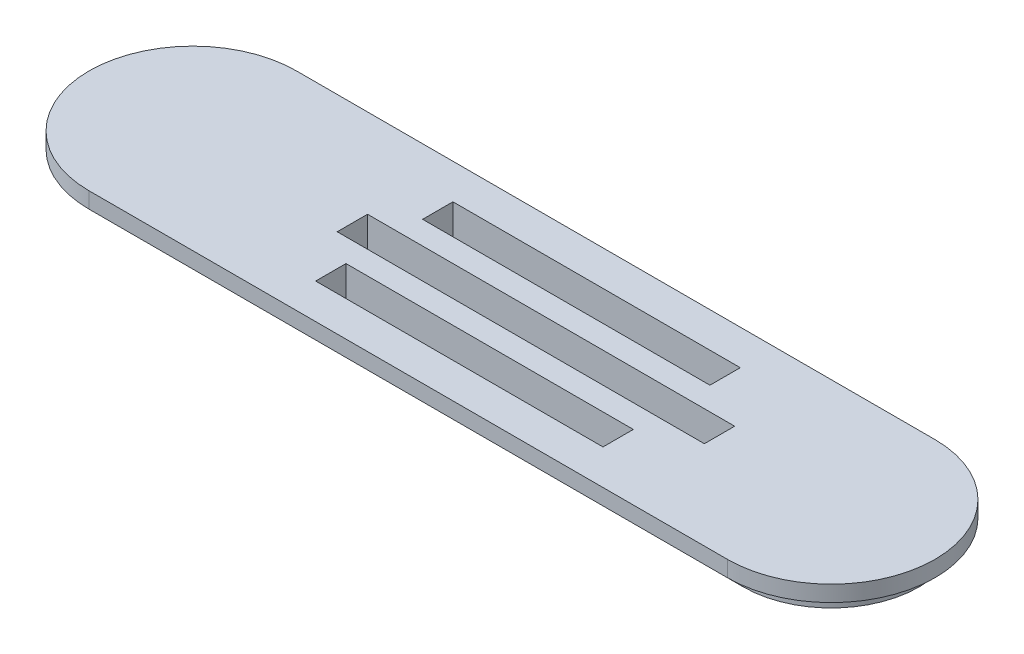
SolidWorks part; units mm, degrees
ref_plane "Front Plane" through (0, 0, 0) normal (0, 0, 1) x (1, 0, 0)
ref_plane "Top Plane" through (0, 0, 0) normal (0, 1, 0) x (1, 0, 0)
ref_plane "Right Plane" through (0, 0, 0) normal (1, 0, 0) x (0, 0, -1)
sketch "Sketch1" plane through (0, 0, 0) normal (0, 1, 0) x (1, 0, 0)
  line L0 (-100, 32.5) -> (100, 32.5)
  line L1 (-100, -32.5) -> (100, -32.5)
  line L6 (0, 21.5) -> (-40, 21.5)
  line L7 (-40, 21.5) -> (-40, 12)
  line L8 (-40, 12) -> (0, 12)
  line L9 (0, 12) -> (50, 12)
  line L10 (50, 12) -> (50, 21.5)
  line L11 (50, 21.5) -> (0, 21.5)
  line L12 (-50, 4.75) -> (0, 4.75)
  line L13 (0, 4.75) -> (65, 4.75)
  line L14 (65, 4.75) -> (65, -4.75)
  line L15 (65, -4.75) -> (0, -4.75)
  line L16 (0, -4.75) -> (-50, -4.75)
  line L17 (-50, -4.75) -> (-50, 4.75)
  line L21 (0, -12) -> (-40, -12)
  line L22 (-40, -12) -> (-40, -21.5)
  line L23 (-40, -21.5) -> (0, -21.5)
  line L24 (0, -21.5) -> (50, -21.5)
  line L25 (50, -21.5) -> (50, -12)
  line L26 (50, -12) -> (0, -12)
  line L27 (100, 13.6373) -> (100, -13.3202) construction
  line L28 (82.1775, 0) -> (117.959, 0) construction
  arc A0 (100, 32.5) -> (100, -32.5) centre (100, 0) cw
  arc A1 (-100, 32.5) -> (-100, -32.5) centre (-100, 0) ccw
  dimension "D7" = 4.75
  dimension "D1" = 32.5
  dimension "D2" = 32.5
  dimension "D3" = 100
  dimension "D4" = 100
  dimension "D25" = 9.5
  dimension "D26" = 9.5
  dimension "D27" = 9.5
  dimension "D28" = 50
  dimension "D29" = 0
  dimension "D30" = 0
  dimension "D31" = 40
  dimension "D32" = 65
  dimension "D33" = 0
  dimension "D34" = 0
  dimension "D35" = 50
  dimension "D36" = 40
  dimension "D37" = 0
  dimension "D38" = 0
  dimension "D39" = 50
  dimension "D40" = 11
  dimension "D41" = 11
extrude "Boss-Extrude1" add sketch "Sketch1" along normal blind 10
sketch "Sketch2" plane through (0, 0, 0) normal (0, 1, 0) x (1, 0, 0)
  line L0 (-100, 32.5) -> (100, 32.5)
  line L1 (100, -32.5) -> (-100, -32.5)
  line L2 (-100, 27.5) -> (100, 27.5)
  line L3 (-100, -27.5) -> (100, -27.5)
  arc A0 (100, 32.5) -> (100, -32.5) centre (100, 0) cw
  arc A1 (100, -32.5) -> (100, 32.5) centre (100, 0) ccw construction
  arc A2 (-100, -32.5) -> (-100, 32.5) centre (-100, 0) cw
  arc A3 (-100, 27.5) -> (-100, -27.5) centre (-100, 0) ccw
  arc A4 (100, 27.5) -> (100, -27.5) centre (100, 0) cw
  dimension "D1" = 5
  dimension "D2" = 5
extrude "Cut-Extrude1" cut sketch "Sketch2" along normal blind 5
